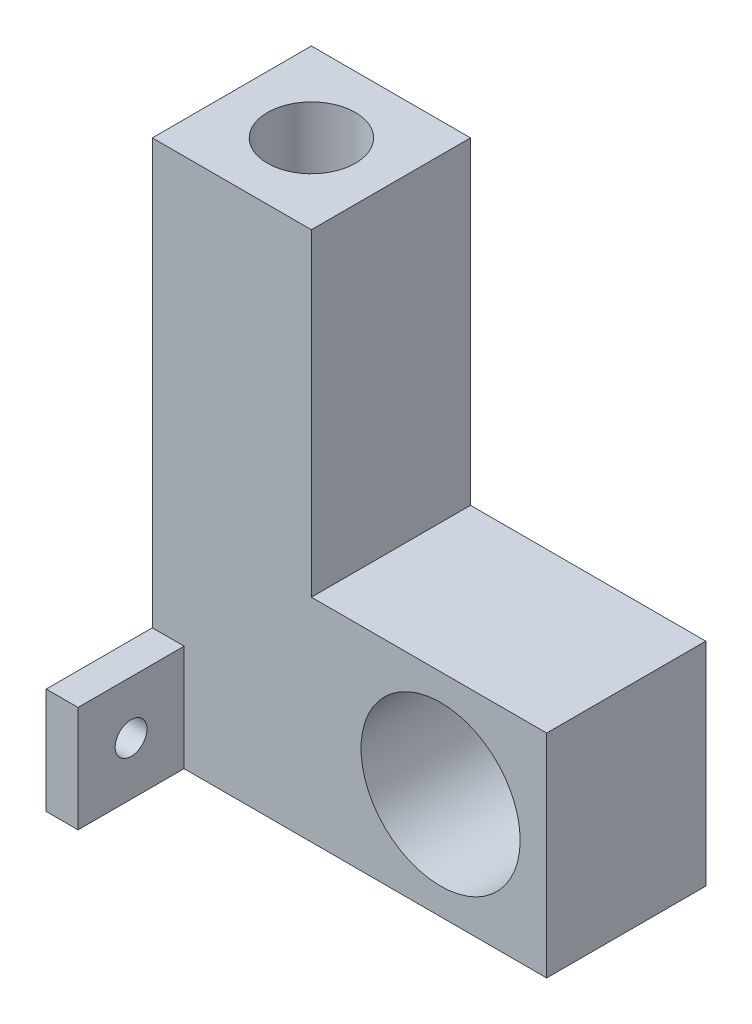
SolidWorks part; units mm, degrees
ref_plane "Front Plane" through (0, 0, 0) normal (0, 0, 1) x (1, 0, 0)
ref_plane "Top Plane" through (0, 0, 0) normal (0, 1, 0) x (1, 0, 0)
ref_plane "Right Plane" through (0, 0, 0) normal (1, 0, 0) x (0, 0, -1)
sketch "Sketch1" plane through (0, 0, 0) normal (0, 0, 1) x (1, 0, 0)
  line L0 (-12.1801, -10) -> (150.2507, -10) construction
  line L1 (0, 0) -> (200.754, 0) construction
  line L3 (0, 121.8331) -> (200.754, 121.8331) construction
  line L4 (200.754, 0) -> (200.754, 121.8331) construction
  line L5 (-12.1801, -10) -> (10, -10)
  line L6 (-12.1801, -10) -> (-12.1801, 10)
  line L7 (-12.1801, 10) -> (10, 10)
  line L8 (10, -10) -> (10, 10)
  line L10 (-12.1801, 10) -> (10, 10)
  line L18 (41.5355, 68.3037) -> (44.4022, 68.3037)
  line L19 (41.5355, 68.3037) -> (41.5355, 71.1731)
  line L20 (41.5355, 71.1731) -> (44.4022, 71.1731)
  line L21 (44.4022, 68.3037) -> (44.4022, 71.1731)
  line L22 (-12.1801, -10) -> (-27.1801, -10)
  line L23 (-12.1801, -10) -> (-12.1801, 40)
  line L24 (-12.1801, 40) -> (-27.1801, 40)
  line L25 (-27.1801, -10) -> (-27.1801, 40)
  circle A0 centre (0, 0) radius 7.5
  circle A1 centre (0, 0) radius 10
  circle A2 centre (0, 42.5) radius 32.5 construction
  circle A3 centre (14.5359, 39.9369) radius 32.5 construction
  circle A4 centre (27.3185, 32.5569) radius 32.5 construction
  circle A5 centre (36.8061, 21.25) radius 32.5 construction
  circle A6 centre (41.5355, 68.3037) radius 8
  circle A7 centre (41.5355, 68.3037) radius 14.65
  circle A8 centre (56.8061, 21.25) radius 32.5 construction
  circle A9 centre (76.8061, 21.25) radius 32.5 construction
  circle A10 centre (96.8061, 21.25) radius 32.5 construction
  circle A11 centre (116.8061, 21.25) radius 32.5 construction
  point P22 (0, 0)
  dimension "D1" = 15
  dimension "D3" = 20
  dimension "D8" = 65
  dimension "D10" = 16
  dimension "D11" = 29.3
  dimension "D2" = 0
  dimension "D4" = 10
  dimension "D5" = 15
  dimension "D6" = 50
  dimension "D7" = 10
  dimension "D12" = 5
  dimension "D9" = 4
extrude "Boss-Extrude1" add sketch "Sketch1" along normal blind 15 contours L25 L22 L6 L23 L24 | A1 L7 L6 L5 | A1 L5 L8 | A1 L8 L10 | A0
sketch "Sketch2" plane through (0, 40, 0) normal (0, 1, 0) x (1, 0, 0)
  line L0 (-12.1801, -15) -> (-27.1801, -15) construction
  line L1 (-12.1801, -15) -> (-12.1801, 0) construction
  circle A0 centre (-19.6801, -7.5) radius 4.15
  dimension "D1" = 7.5
  dimension "D3" = 8.3
  dimension "D2" = 7.5
extrude "Cut-Extrude1" cut sketch "Sketch2" against normal through all
sketch "Sketch3" plane through (-27.1801, 0, 0) normal (-1, 0, 0) x (0, 0, 1)
  line L0 (15, 40) -> (0, 40) construction
  line L1 (-10, -10) -> (25, -10)
  line L2 (-10, -10) -> (-10, 0)
  line L3 (-10, 0) -> (25, 0)
  line L4 (25, -10) -> (25, 0)
  line L5 (0, -10) -> (0, 40) construction
  line L6 (15, -10) -> (15, 40) construction
  line L7 (15, -10) -> (0, -10) construction
  circle A0 centre (-5, -5) radius 1.5
  circle A1 centre (20, -5) radius 1.5
  dimension "D5" = 3
  dimension "D6" = 3
  dimension "D7" = 5
  dimension "D8" = 5
  dimension "D9" = 5
  dimension "D10" = 5
  dimension "D1" = 40
  dimension "D2" = 10
  dimension "D3" = 10
  dimension "D4" = 0
extrude "Boss-Extrude2" add sketch "Sketch3" against normal blind 3
